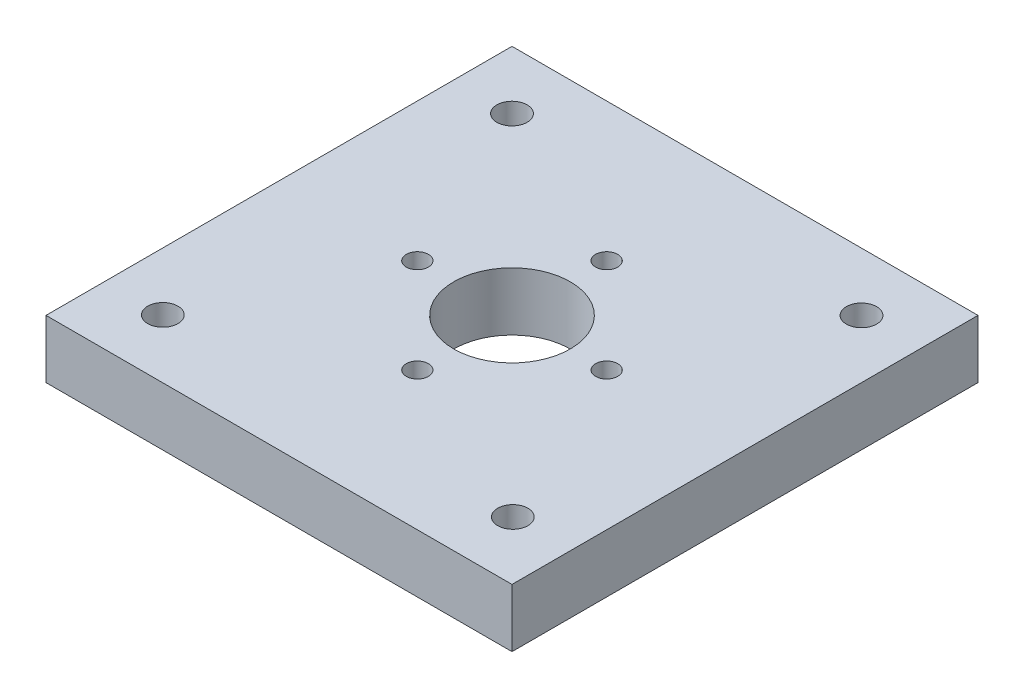
SolidWorks part; units mm, degrees
ref_plane "Front Plane" through (0, 0, 0) normal (0, 0, 1) x (1, 0, 0)
ref_plane "Top Plane" through (0, 0, 0) normal (0, 1, 0) x (1, 0, 0)
ref_plane "Right Plane" through (0, 0, 0) normal (1, 0, 0) x (0, 0, -1)
sketch "Sketch2" plane through (0, 0, 0) normal (0, 1, 0) x (1, 0, 0)
  line L1 (-50.8, 50.8) -> (50.8, 50.8)
  line L2 (-50.8, 50.8) -> (-50.8, -50.8)
  line L3 (-50.8, -50.8) -> (50.8, -50.8)
  line L4 (50.8, 50.8) -> (50.8, -50.8)
  point P0 (0, 0)
  dimension "D1" = 101.6
  dimension "D2" = 50.8
  dimension "D3" = 101.6
  dimension "D4" = 50.8
extrude "Boss-Extrude1" add sketch "Sketch2" along normal blind 12.7
sketch "Sketch3" plane through (0, 12.7, 0) normal (0, 1, 0) x (1, 0, 0)
  line L5 (50.8, -50.8) -> (50.8, 50.8) construction
  circle A0 centre (-38.1, 38.1) radius 3.302
  circle A1 centre (-38.1548, -37.9718) radius 3.302
  circle A2 centre (38.1548, -37.9718) radius 3.302
  circle A3 centre (38.1, 38.1) radius 3.302
  point P2 (-118.0262, 48.6699)
  point P3 (-136.729, -37.9718)
  point P5 (-206.3976, -97.8124)
  point P6 (-204.1941, -68.6768)
  point P11 (-204.1941, -68.6768)
  point P12 (50.8, 38.1)
  point P13 (-38.1, -50.6535)
  point P14 (-206.3976, -97.8124)
  dimension "D3" = 6.604
  dimension "D1" = 6.604
  dimension "D2" = 6.604
  dimension "D4" = 6.604
  dimension "D5" = 12.6452
  dimension "D6" = 12.7
  dimension "D7" = 88.9
  dimension "D8" = 88.9548
  dimension "D9" = 12.7
  dimension "D10" = 88.7718
extrude "Cut-Extrude1" cut sketch "Sketch3" against normal blind 12.7 contours A0 | A2 | A1 | A3
sketch "Sketch4" plane through (0, 12.7, 0) normal (0, 1, 0) x (1, 0, 0)
  circle A0 centre (0, 0) radius 12.7
  dimension "D1" = 25.4
extrude "Cut-Extrude2" cut sketch "Sketch4" against normal blind 12.7
sketch "Sketch5" plane through (0, 12.7, 0) normal (0, 1, 0) x (1, 0, 0)
  line L0 (50.8, -50.8) -> (50.8, 50.8) construction
  circle A1 centre (0, 20.6375) radius 2.413
  circle A2 centre (20.6375, 0) radius 2.413
  circle A3 centre (0, -20.6375) radius 2.413
  circle A4 centre (-20.6375, 0) radius 2.413
  point P14 (0, 0)
  dimension "D1" = 30.1625
  dimension "D2" = 4.826
  dimension "D4" = 50.8
  dimension "D5" = 30.1625
  dimension "D3" = 4
extrude "Cut-Extrude3" cut sketch "Sketch5" against normal blind 63.5
